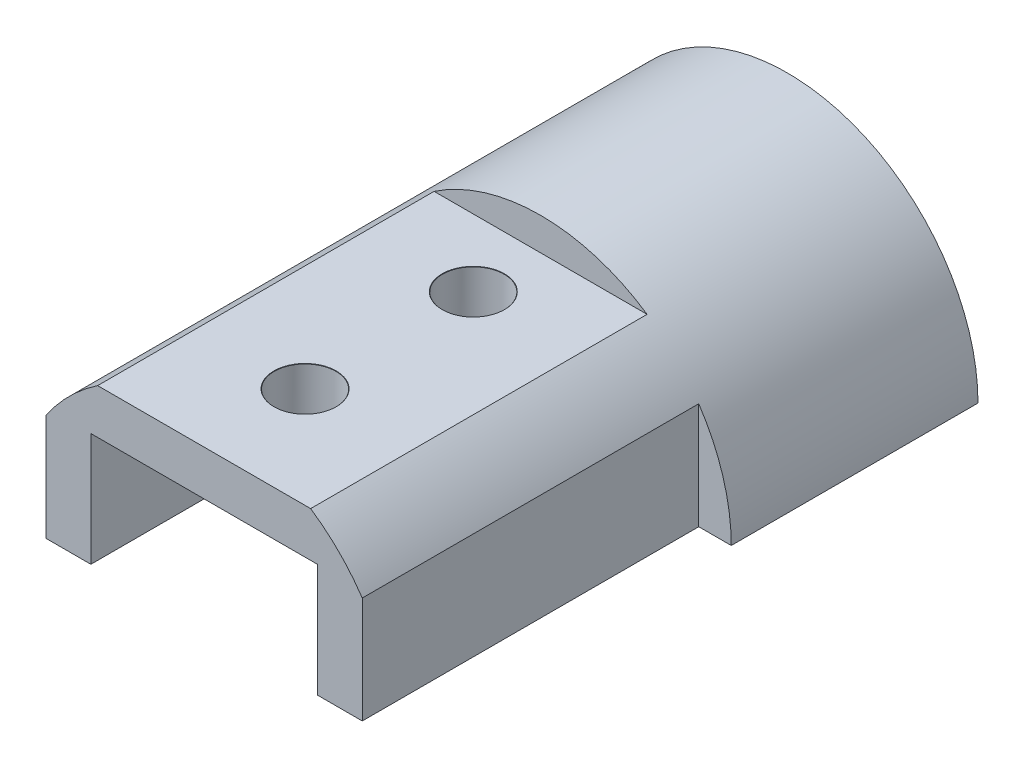
SolidWorks part; units mm, degrees
ref_plane "前视基准面" through (0, 0, 0) normal (0, 0, 1) x (1, 0, 0)
ref_plane "上视基准面" through (0, 0, 0) normal (0, 1, 0) x (1, 0, 0)
ref_plane "右视基准面" through (0, 0, 0) normal (1, 0, 0) x (0, 0, -1)
sketch "草图1" plane through (0, 0, 0) normal (0, 0, 1) x (1, 0, 0)
  circle A0 centre (0, 0) radius 17
  dimension "D1" = 34
extrude "凸台-拉伸1" add sketch "草图1" along normal blind 2
sketch "草图2" plane through (0, 0, 2) normal (0, 0, 1) x (1, 0, 0)
  circle A0 centre (0, 0) radius 17 construction
  circle A1 centre (0, 0) radius 17
  circle A2 centre (0, 0) radius 15
  dimension "D1" = 30
extrude "凸台-拉伸2" add sketch "草图2" along normal blind 10
sketch "草图3" plane through (0, 0, 2) normal (0, 0, 1) x (1, 0, 0)
  circle A0 centre (0, 0) radius 5
  dimension "D1" = 10
extrude "切除-拉伸1" cut sketch "草图3" against normal through all
sketch "草图4" plane through (0, 0, 12) normal (0, 0, 1) x (1, 0, 0)
  line L0 (0, 17) -> (0, -17) construction
  line L1 (-17, 0) -> (0, 0) construction
  line L2 (-4.4431, 10.1) -> (4.4431, 10.1)
  line L7 (10.1, 4.4431) -> (10.1, -4.4431)
  line L8 (-10.1, 4.4431) -> (-10.1, -4.4431)
  line L9 (-4.4431, 10.1) -> (-10.1, 4.4431)
  line L10 (4.4431, 10.1) -> (10.1, 4.4431)
  line L11 (-4.4431, -10.1) -> (-10.1, -4.4431)
  line L12 (-4.4431, -10.1) -> (4.4431, -10.1)
  line L13 (4.4431, -10.1) -> (10.1, -4.4431)
  circle A0 centre (0, 0) radius 17
  point P17 (0, 10.1)
  point P18 (-10.1, 0)
  point P21 (10.1, 0)
  dimension "D1" = 10.1
  dimension "D2" = 10.1
  dimension "D3" = 8
  dimension "D4" = 135
extrude "凸台-拉伸3" add sketch "草图4" along normal blind 10
sketch "草图5" plane through (0, 0, 22) normal (0, 0, 1) x (1, 0, 0)
  line L2 (-9.4968, 14.1) -> (9.4968, 14.1)
  line L4 (-14.1, 9.4968) -> (-14.1, -9.4968)
  line L6 (0, 0) -> (10.1, 10.1) construction
  line L7 (14.1, -9.4968) -> (14.1, 9.4968)
  line L8 (9.4968, -14.1) -> (-9.4968, -14.1)
  line L11 (-10.1, 10.1) -> (-10.1, -10.1)
  line L12 (-10.1, -10.1) -> (10.1, -10.1)
  line L13 (10.1, -10.1) -> (10.1, 10.1)
  line L14 (10.1, 10.1) -> (-10.1, 10.1)
  circle A1 centre (0, 0) radius 17 construction
  arc A2 (-14.1, -9.4968) -> (-9.4968, -14.1) centre (0, 0) ccw
  arc A3 (-9.4968, 14.1) -> (-14.1, 9.4968) centre (0, 0) ccw
  arc A4 (14.1404, 9.4366) -> (9.4366, 14.1404) centre (0, 0) ccw
  arc A5 (14.1, -9.4968) -> (9.4968, -14.1) centre (0, 0) cw
  dimension "D1" = 4
  dimension "D2" = 4
  dimension "D3" = 20.2
  dimension "D4" = 20.2
extrude "凸台-拉伸4" add sketch "草图5" along normal blind 30
hole_wizard "M5 间隙孔2" positions "草图6" profile "草图7" hole size "M5" standard "ISO" end condition through all
sketch "草图6" plane through (0, 14.1, 0) normal (0, 1, 0) x (1, 0, 0)
  line L2 (-9.4968, -22) -> (9.4968, -22) construction
  point P0 (0, -28)
  point P2 (0, -43)
  dimension "D1" = 6
  dimension "D2" = 15
sketch "草图7" plane through (0, 14.1, 28) normal (1, 0, 0) x (0, 0, 1)
  line L0 (0, 0) -> (0, 31.1)
  line L1 (0, 31.1) -> (2.75, 31.1)
  line L2 (2.75, 31.1) -> (2.75, 0.025)
  line L3 (2.75, 0.025) -> (2.775, 0)
  line L5 (2.775, 0) -> (0, 0)
  line L6 (-2.75, 0.025) -> (-2.775, 0) construction
  line L11 (0, -6.35) -> (0, 107.95) construction
  dimension "通孔孔直径" = 5.5
  dimension "通孔孔深度" = 31.1
  dimension "近端锥形沉头孔直径" = 5.55
  dimension "近端锥形沉头孔角度" = 90
hole_wizard "M2.5 间隙孔2" positions "草图9" profile "草图10" hole size "M2.5" standard "ISO" end condition through all
sketch "草图9" plane through (0, 0, 2) normal (0, 0, 1) x (1, 0, 0)
  line L0 (0, 8) -> (0, 0) construction
  line L2 (0, 0) -> (5.6569, 5.6569) construction
  point P30 (0, 8)
  point P40 (5.6569, 5.6569)
  point P41 (8, 0)
  point P42 (5.6569, -5.6569)
  point P43 (0, -8)
  point P44 (-5.6569, -5.6569)
  point P45 (-8, 0)
  point P46 (-5.6569, 5.6569)
  point P55 (0, 0)
  dimension "D1" = 8
  dimension "D3" = 45
  dimension "D2" = 8
sketch "草图10" plane through (0, 8, 2) normal (1, 0, 0) x (0, -1, 0)
  line L0 (0, 0) -> (0, 2)
  line L1 (0, 2) -> (1.45, 2)
  line L2 (1.45, 2) -> (1.45, 0.025)
  line L3 (1.45, 0.025) -> (1.475, 0)
  line L5 (1.475, 0) -> (0, 0)
  line L6 (-1.45, 0.025) -> (-1.475, 0) construction
  line L11 (0, -6.35) -> (0, 107.95) construction
  dimension "通孔孔直径" = 2.9
  dimension "通孔孔深度" = 2
  dimension "近端锥形沉头孔直径" = 2.95
  dimension "近端锥形沉头孔角度" = 90
sketch "Sketch1" plane through (0, 0, 0) normal (0, 1, 0) x (0, 0, -1)
  line L2 (-62.5, -20) -> (2.5, -20)
  line L3 (-62.5, -20) -> (-62.5, 20)
  line L4 (-62.5, 20) -> (2.5, 20)
  line L5 (2.5, -20) -> (2.5, 20)
  line L6 (-62.5, -20) -> (2.5, 20) construction
  line L7 (-62.5, 20) -> (2.5, -20) construction
  point P0 (-30, 0)
  point P5 (0, 0)
  dimension "D1" = 30
  dimension "D2" = 65
  dimension "D3" = 40
extrude "Cut-Extrude2" cut sketch "Sketch1" against normal through all
